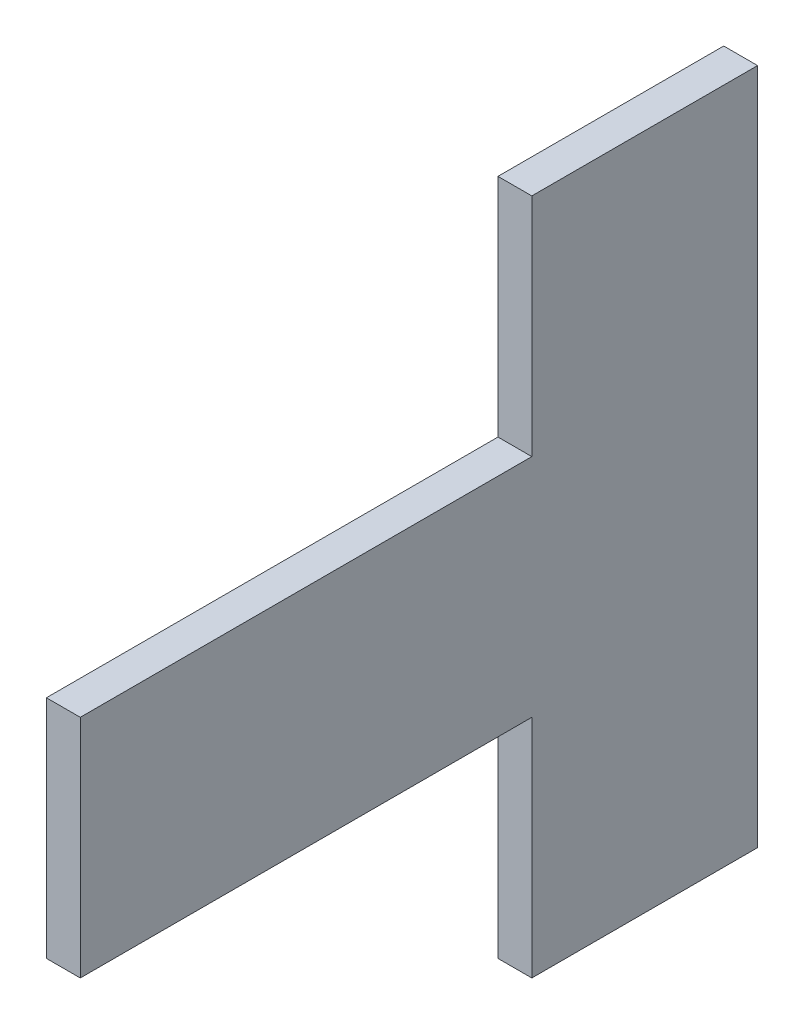
SolidWorks part; units mm, degrees
ref_plane "Front Plane" through (0, 0, 0) normal (0, 0, 1) x (1, 0, 0)
ref_plane "Top Plane" through (0, 0, 0) normal (0, 1, 0) x (1, 0, 0)
ref_plane "Right Plane" through (0, 0, 0) normal (1, 0, 0) x (0, 0, -1)
sketch "Sketch1" plane through (0, 0, 0) normal (1, 0, 0) x (0, 0, -1)
  line L0 (0, 0) -> (-50.8, 0)
  line L1 (-50.8, 0) -> (-50.8, -25.4)
  line L2 (-50.8, -25.4) -> (0, -25.4)
  line L3 (0, -25.4) -> (0, -50.8)
  line L4 (0, -50.8) -> (25.4, -50.8)
  line L5 (25.4, -50.8) -> (25.4, 25.4)
  line L6 (25.4, 25.4) -> (0, 25.4)
  line L7 (0, 25.4) -> (0, 0)
  dimension "D1" = 25.4
  dimension "D2" = 25.4
  dimension "D3" = 76.2
  dimension "D4" = 76.2
  dimension "D5" = 25.4
extrude "Boss-Extrude1" add sketch "Sketch1" along normal blind 3.81
